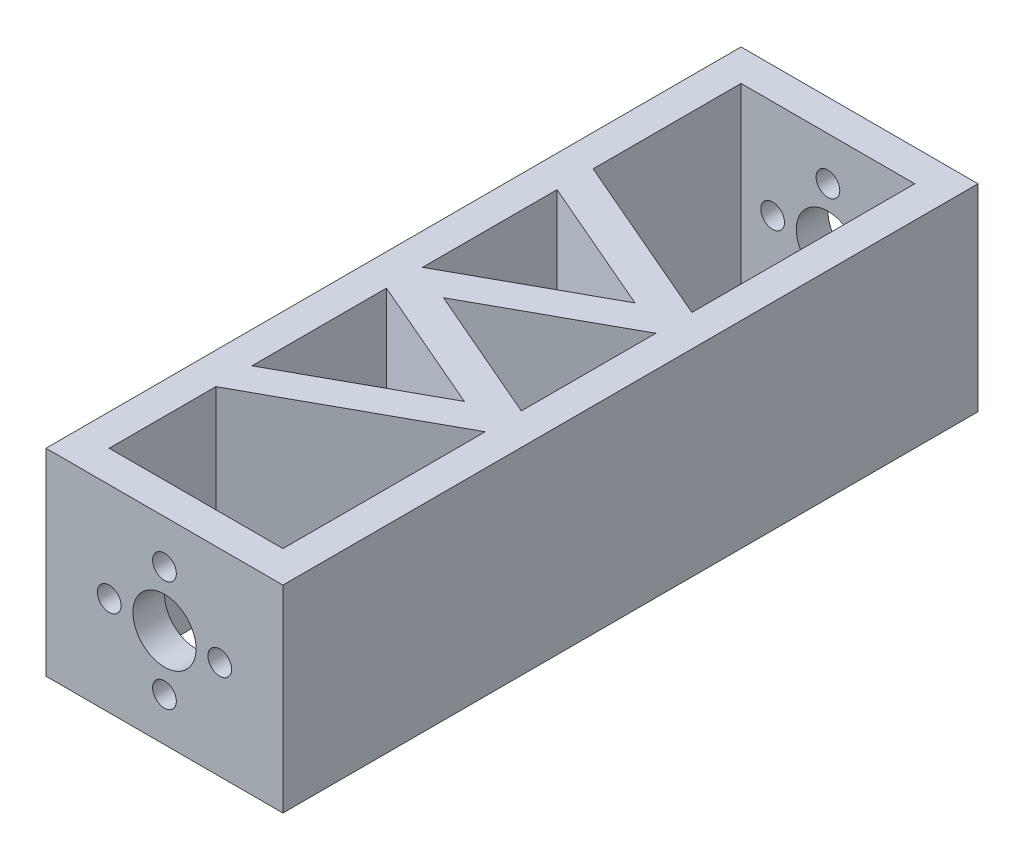
SolidWorks part; units mm, degrees
ref_plane "前视基准面" through (0, 0, 0) normal (0, 0, 1) x (1, 0, 0)
ref_plane "上视基准面" through (0, 0, 0) normal (0, 1, 0) x (1, 0, 0)
ref_plane "右视基准面" through (0, 0, 0) normal (1, 0, 0) x (0, 0, -1)
other "Configuration Table"
sketch "草图1" plane through (0, 0, 0) normal (0, 0, 1) x (1, 0, 0)
  line L0 (0, -11.2948) -> (0, 11.2948) construction
  line L1 (-26.4287, 0) -> (28.5713, 0) construction
  line L3 (-15, -12.5) -> (15, -12.5)
  line L4 (-15, -12.5) -> (-15, 12.5)
  line L5 (-15, 12.5) -> (15, 12.5)
  line L6 (15, -12.5) -> (15, 12.5)
  line L7 (-15, -12.5) -> (15, 12.5) construction
  line L8 (-15, 12.5) -> (15, -12.5) construction
  circle A0 centre (0, 0) radius 7 construction
  circle A1 centre (7, 0) radius 1.5
  circle A2 centre (0, 7) radius 1.5
  circle A3 centre (-7, 0) radius 1.5
  circle A4 centre (0, -7) radius 1.5
  circle A7 centre (0, 0) radius 4
  point P20 (0, 0)
  dimension "D1" = 3
  dimension "D4" = 14
  dimension "D5" = 8
  dimension "D2" = 30
  dimension "D3" = 25
extrude "凸台-拉伸1" add sketch "草图1" along normal blind 4
sketch "草图2" plane through (0, 0, 4) normal (0, 0, 1) x (1, 0, 0)
  line L0 (-15, -12.5) -> (15, -12.5) construction
  line L1 (-15, 12.5) -> (-11, 12.5)
  line L2 (-15, 12.5) -> (-15, -12.5)
  line L3 (-15, -12.5) -> (-11, -12.5)
  line L4 (-11, 12.5) -> (-11, -12.5)
  line L5 (0, 14.6778) -> (0, -17.2978) construction
  line L6 (11, 12.5) -> (11, -12.5)
  line L7 (15, -12.5) -> (11, -12.5)
  line L8 (15, 12.5) -> (15, -12.5)
  line L9 (15, 12.5) -> (11, 12.5)
  dimension "D1" = 4
extrude "凸台-拉伸2" add sketch "草图2" along normal blind 80
sketch "草图3" plane through (0, 0, 84) normal (0, 0, 1) x (1, 0, 0)
  line L1 (-15, 12.5) -> (15, 12.5)
  line L2 (-15, 12.5) -> (-15, -12.5)
  line L3 (-15, -12.5) -> (15, -12.5)
  line L4 (15, 12.5) -> (15, -12.5)
extrude "凸台-拉伸3" add sketch "草图3" along normal blind 4
sketch "草图4" plane through (0, 0, 88) normal (0, 0, 1) x (1, 0, 0)
  circle A0 centre (-7, 0) radius 1.5 construction
  circle A1 centre (0, -7) radius 1.5 construction
  circle A2 centre (7, 0) radius 1.5 construction
  circle A3 centre (0, 0) radius 4 construction
  circle A4 centre (0, 7) radius 1.5 construction
  circle A5 centre (-7, 0) radius 1.5
  circle A6 centre (0, -7) radius 1.5
  circle A7 centre (7, 0) radius 1.5
  circle A8 centre (0, 0) radius 4
  circle A9 centre (0, 7) radius 1.5
extrude "切除-拉伸1" cut sketch "草图4" against normal blind 11
sketch "草图9" plane through (0, -12.5, 0) normal (0, -1, 0) x (1, 0, 0)
  line L0 (-11, 70.4934) -> (11, 58.3856)
  line L1 (-11, 84) -> (-11, 4) construction
  line L2 (11, 84) -> (11, 4) construction
  line L3 (11, 58.3856) -> (11, 53.8198)
  line L4 (11, 53.8198) -> (-11, 65.9277)
  line L5 (-11, 65.9277) -> (-11, 70.4934)
  line L6 (11, 58.3856) -> (-11, 48.8945)
  line L7 (11, 53.8198) -> (-11, 44.3287)
  line L8 (-11, 44.3287) -> (-11, 48.8945)
  line L9 (-11, 48.8945) -> (11, 36.7866)
  line L10 (-11, 44.3287) -> (11, 32.2208)
  line L11 (11, 32.2208) -> (11, 36.7866)
  line L12 (11, 36.7866) -> (-11, 27.2955)
  line L13 (11, 32.2208) -> (-11, 22.7297)
  line L14 (-11, 22.7297) -> (-11, 27.2955)
  line M11 (-11, 4) -> (-11, 84)
  line M13 (11, 84) -> (11, 4)
  dimension "D1" = 4
extrude "凸台-拉伸4" add sketch "草图9" against normal blind 25 contours L6 L0 L4 M11 | L6 L4 M13 | L6 L9 L7 L4 | L9 L7 M11 | L12 L9 L7 L10 | L12 L10 M13 | L13 L10 L12 M11
